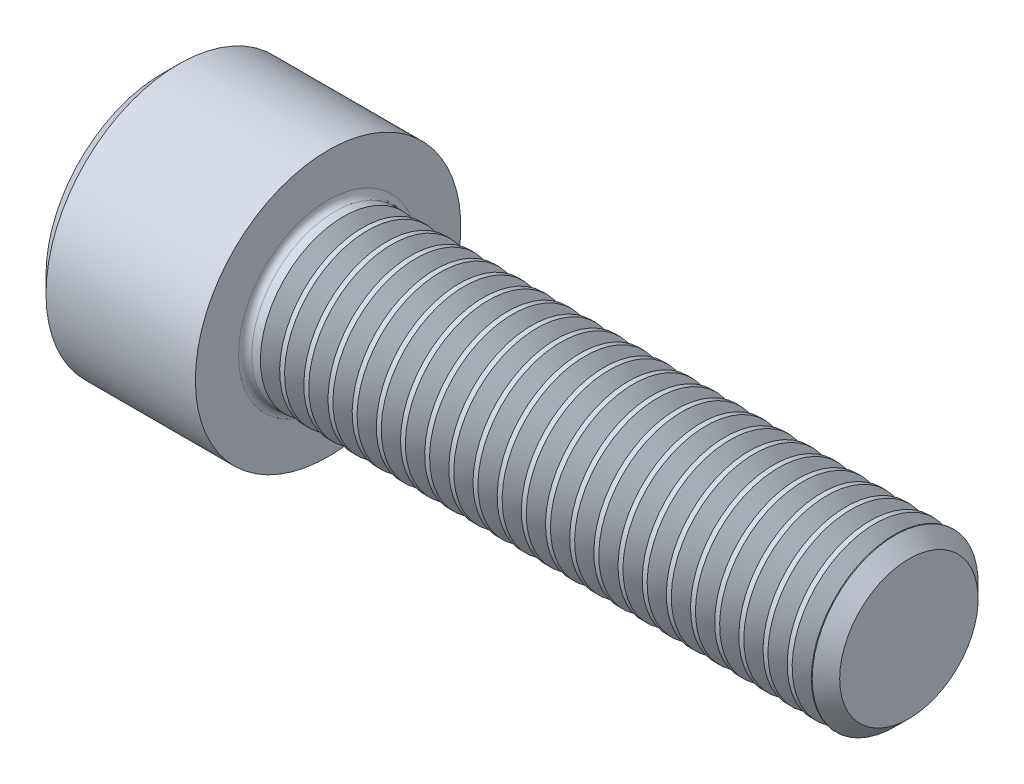
SolidWorks part; units mm, degrees
revolve "Base-Revolve" add sketch "BodySke"
sketch "BodySke" plane through (0, 0, 0) normal (0, 0, 1) x (1, 0, 0)
  line L0 (0, 0) -> (0, 7)
  line L1 (1, 8) -> (10, 8)
  line L2 (10, 8) -> (10, 5)
  line L3 (10, 5) -> (44.172, 5)
  line L4 (45, 4.172) -> (45, 0)
  line L5 (45, 0) -> (0, 0)
  line L6 (-31.75, 0) -> (127, 0) construction
  line L7 (0, 7) -> (1, 8)
  line L8 (45, 4.172) -> (44.172, 5)
  line L9 (0, -7) -> (1, -8) construction
  line L10 (45, -4.172) -> (44.172, -5) construction
  line L11 (11.5, 9.525) -> (11.5, 3.175) construction
  line L12 (10, 9.525) -> (10, 3.175) construction
  line L13 (-5, 9.525) -> (-5, 3.175) construction
  dimension "Diameter" = 10
  dimension "Head_ht" = 10
  dimension "Length" = 35
  dimension "Body_ch_ang" = 45
  dimension "Head_dia" = 16
  dimension "Head_ch_ang" = 45
  dimension "Minor_dia" = 8.344
  dimension "Advance" = 1.5
  dimension "Thread_nom" = 35
  dimension "Thread_length" = 50
  dimension "Head_ch_ht" = 1
cosmetic thread "ThreadCosmetic" [suppressed]
fillet "Fillet1" radius 0.4 1 edges at (10, 0, 5)
ref_plane "Plane1" through (0, 0, 0) normal (0, 0, 1) x (1, 0, 0)
ref_plane "Plane2" through (0, 0, 0) normal (0, 1, 0) x (1, 0, 0)
ref_plane "Plane3" through (0, 0, 0) normal (1, 0, 0) x (0, 0, -1)
sketch "Sketch2" plane through (0, 0, 0) normal (0, 0, 1) x (1, 0, 0)
  line L0 (0, 4.0575) -> (5, 4.0575)
  line L1 (5, 4.0575) -> (7.3426, 0)
  line L2 (-31.75, 0) -> (127, 0) construction
  line L3 (7.3426, 0) -> (0, 0)
  line L4 (0, 0) -> (0, 4.0575)
  line L5 (0, 7) -> (0, -7) construction
  line L6 (0, 0) -> (47.625, 0) construction
  line L7 (10, -8) -> (10, 8) construction
  dimension "D1" = 4.0575
  dimension "D2" = 60
revolve "Hex-PreBroach" cut sketch "Sketch2" angle 360 about L6
sketch "Sketch3" plane through (0, 0, 0) normal (-1, 0, 0) x (0, 0.5, 0.866)
  line L0 (2.3426, 4.0575) -> (-2.3426, 4.0575)
  line L1 (-2.3426, 4.0575) -> (-4.6852, 0)
  line L2 (2.3426, 4.0575) -> (4.6852, 0)
  line L3 (2.3426, -4.0575) -> (4.6852, 0)
  line L4 (2.3426, -4.0575) -> (-2.3426, -4.0575)
  line L5 (-2.3426, -4.0575) -> (-4.6852, 0)
  dimension "D1" = 4.0575
  dimension "D2" = 4.0575
  dimension "Hex_size" = 8.115
extrude "Hex" cut sketch "Sketch3" against normal blind 5
sketch "Sketch4" plane through (0, 0, 0) normal (-1, 0, 0) x (0, 0, 1)
  line L0 (0, 0) -> (3.7846, 0)
  line L1 (0, 0) -> (6.1484, 3.5498) construction
  line L2 (0, 0) -> (1.8923, 3.2776)
  line L3 (3.1235, 0.8061) -> (3.6229, 1.0945)
  line L4 (2.2599, 2.3019) -> (2.7593, 2.5903)
  arc A0 (3.1235, 0.8061) -> (2.2599, 2.3019) centre (0, 0) ccw
  arc A1 (3.7846, 0) -> (3.6229, 1.0945) centre (0, 0) ccw
  arc A2 (1.8923, 3.2776) -> (2.7593, 2.5903) centre (0, 0) cw
  dimension "D1" = 30
  dimension "D2" = 60
  dimension "Spline_p_dim" = 1.7272
  dimension "D3" = 0.8636
extrude "Spline" [suppressed] cut sketch "Sketch4" against normal blind 5
pattern_circular "CirPattern1" [suppressed] count 6 every 60
sketch "Sketch5" plane through (0, 0, 0) normal (0, 0, 1) x (1, 0, 0)
  line L0 (-31.75, 0) -> (127, 0) construction
  line L2 (0, 7) -> (0, -7) construction
  circle A0 centre (3.3, 0) radius 0.825
  dimension "Drilled_hole_dia" = 1.65
  dimension "Drilled_hole_loc" = 3.3
extrude "Hole" [suppressed] cut sketch "Sketch5" against normal through all and the other way through all
pattern_circular "Drilled-4" [suppressed] count 2 every 60
pattern_circular "Drilled-6" [suppressed] count 3 every 60
sketch "ThdSchSke" plane through (0, 0, 0) normal (0, 0, 1) x (1, 0, 0)
  line L0 (11.5, -4.172) -> (10.9202, -5)
  line L1 (11.5, -4.172) -> (12.0798, -5)
  line L2 (12.0798, -5) -> (12.0798, -6.25)
  line L3 (-3.175, 0) -> (5.1513, 0) construction
  line L5 (12.0798, -6.25) -> (10.9202, -6.25)
  line L6 (10.9202, -6.25) -> (10.9202, -5)
  line L7 (0, 7) -> (0, -7) construction
  dimension "Thread_minor" = 8.344
  dimension "Diameter" = 10
  dimension "Start" = 11.5
revolve "ThreadSchematic" cut sketch "ThdSchSke" angle 360 about L3
pattern_linear "ThdSchPat" count 23 spacing 1.4565 along (1, 0, 0) of "ThreadSchematic"
equation "\"D2@Sketch3\" = \"Hex_size@Sketch3\" / 2"
equation "\"D1@Sketch3\" = \"Hex_size@Sketch3\" / 2"
equation "\"D1@Sketch2\" = \"Hex_size@Sketch3\" / 2"
equation "\"D3@Sketch4\" = \"Spline_p_dim@Sketch4\" / 2"
equation "\"Thread_minor@ThreadCosmetic\"  =  \"Minor_dia@BodySke\""
equation "\"D2@CirPattern1\" = 360 / \"Num_teeth@CirPattern1\""
equation "\"Wall_thickness@Sketch2\" = \"Head_ht@BodySke\" - \"Key_eng@Hex\""
equation "\"Thread_length@ThreadCosmetic\" = ((sgn( (\"Length@BodySke\" - \"Advance@BodySke\" ) - \"Thread_nom@BodySke\" )-1)*( (\"Length@BodySke\" - \"Advance@BodySke\" ) - \"Thread_nom@BodySke\" ))/-2+ \"Thread_nom@BodySke\""
equation "\"Thread_minor@ThdSchSke\" = \"Minor_dia@BodySke\""
equation "\"Diameter@ThdSchSke\" = \"Diameter@BodySke\""
equation "\"Overcut@ThdSchSke\" = \"Diameter@BodySke\" * 1.25"
equation "\"Start@ThdSchSke\" = \"Head_ht@BodySke\" + \"Length@BodySke\" - \"Thread_length@ThreadCosmetic\"  '---Non-countersunk---"
equation "\"Num_threads@ThdSchPat\" = int( \"Thread_length@ThreadCosmetic\" / \"Advance@BodySke\" + 0.999 )  + 1"
equation "\"Advance@ThdSchPat\" = \"Thread_length@ThreadCosmetic\" /  (\"Num_threads@ThdSchPat\" - 1) 'relax it"
equation "\"Num_threads@ThdSchPat\" = \"Num_threads@ThdSchPat\" - sgn( \"Num_threads@ThdSchPat\" - 1) '---chamfered tips only---"
